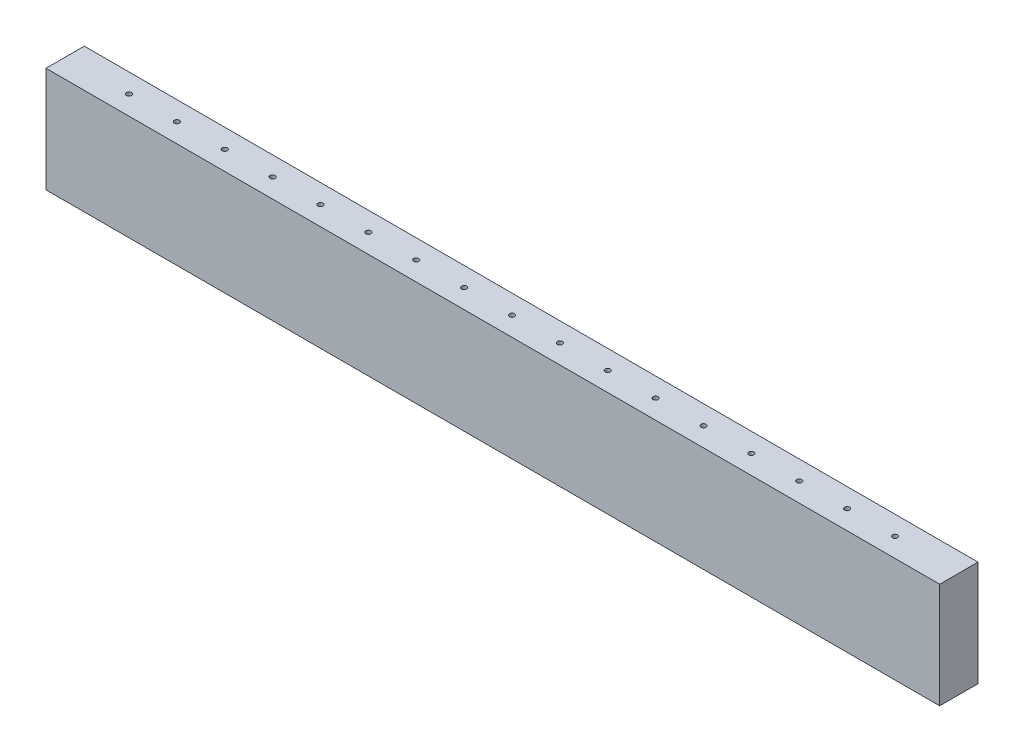
SolidWorks part; units mm, degrees
ref_plane "Front Plane" through (0, 0, 0) normal (0, 0, 1) x (1, 0, 0)
ref_plane "Top Plane" through (0, 0, 0) normal (0, 1, 0) x (1, 0, 0)
ref_plane "Right Plane" through (0, 0, 0) normal (1, 0, 0) x (0, 0, -1)
sketch "Sketch1" plane through (0, 0, 0) normal (0, 1, 0) x (1, 0, 0)
  line L1 (-140, 6) -> (140, 6)
  line L2 (-140, 6) -> (-140, -6)
  line L3 (-140, -6) -> (140, -6)
  line L4 (140, 6) -> (140, -6)
  line L5 (-140, 6) -> (140, -6) construction
  line L6 (-140, -6) -> (140, 6) construction
  point P0 (0, 0)
  dimension "D1" = 280
  dimension "D2" = 12
extrude "Boss-Extrude1" add sketch "Sketch1" along normal blind 33
hole_wizard "M2 Tapped Hole1" positions "Sketch3" profile "Sketch4" tap size "M2" standard "ISO"
sketch "Sketch3" plane through (0, 33, 0) normal (0, 1, 0) x (1, 0, 0)
  point P2 (0, 0)
  point P6 (0, 0)
sketch "Sketch4" plane through (0, 33, 0) normal (1, 0, 0) x (0, 0, 1)
  line L0 (0, 0) -> (0, 15.4807)
  line L1 (0, 15.4807) -> (0.8, 15)
  line L2 (0.8, 15) -> (0.8, 0)
  line L5 (0.8, 0) -> (0, 0)
  line L10 (0, 15.4807) -> (-0.8, 15) construction
  line L11 (0, -6.35) -> (0, 107.95) construction
  dimension "Tap Drill Dia." = 1.6
  dimension "Tap Drill Depth" = 15
  dimension "Drill Angle" = 118
cosmetic thread "Hole Thread1" parameters "D1"=4, "D2"=2
pattern_linear "LPattern1" count 9 spacing 15 along (1, 0, 0) count 9 spacing 15 along (-1, 0, 0) of "M2 Tapped Hole1"
cosmetic thread "Hole Thread2" parameters "D1"=4, "D2"=2
cosmetic thread "Hole Thread3" parameters "D1"=4, "D2"=2
cosmetic thread "Hole Thread4" parameters "D1"=4, "D2"=2
cosmetic thread "Hole Thread5" parameters "D1"=4, "D2"=2
cosmetic thread "Hole Thread6" parameters "D1"=4, "D2"=2
cosmetic thread "Hole Thread7" parameters "D1"=4, "D2"=2
cosmetic thread "Hole Thread8" parameters "D1"=4, "D2"=2
cosmetic thread "Hole Thread9" parameters "D1"=4, "D2"=2
cosmetic thread "Hole Thread10" parameters "D1"=4, "D2"=2
cosmetic thread "Hole Thread11" parameters "D1"=4, "D2"=2
cosmetic thread "Hole Thread12" parameters "D1"=4, "D2"=2
cosmetic thread "Hole Thread13" parameters "D1"=4, "D2"=2
cosmetic thread "Hole Thread14" parameters "D1"=4, "D2"=2
cosmetic thread "Hole Thread15" parameters "D1"=4, "D2"=2
cosmetic thread "Hole Thread16" parameters "D1"=4, "D2"=2
cosmetic thread "Hole Thread17" parameters "D1"=4, "D2"=2
hole_wizard "M4 Tapped Hole1" positions "Sketch5" profile "Sketch6" tap size "M4" standard "ISO"
sketch "Sketch5" plane through (0, 0, 0) normal (0, -1, 0) x (-1, 0, 0)
  point P0 (-120, 0)
  point P2 (120, 0)
  point P10 (47.0794, -77.8903)
  dimension "D1" = 120
  dimension "D2" = 120
sketch "Sketch6" plane through (120, 0, 0) normal (1, 0, 0) x (0, 0, -1)
  line L0 (0, 0) -> (0, 15.9914)
  line L1 (0, 15.9914) -> (1.65, 15)
  line L2 (1.65, 15) -> (1.65, 0)
  line L5 (1.65, 0) -> (0, 0)
  line L10 (0, 15.9914) -> (-1.65, 15) construction
  line L11 (0, -6.35) -> (0, 107.95) construction
  dimension "Tap Drill Dia." = 3.3
  dimension "Tap Drill Depth" = 15
  dimension "Drill Angle" = 118
cosmetic thread "Hole Thread18" parameters "D1"=8, "D2"=4
cosmetic thread "Hole Thread19" parameters "D1"=8, "D2"=4
